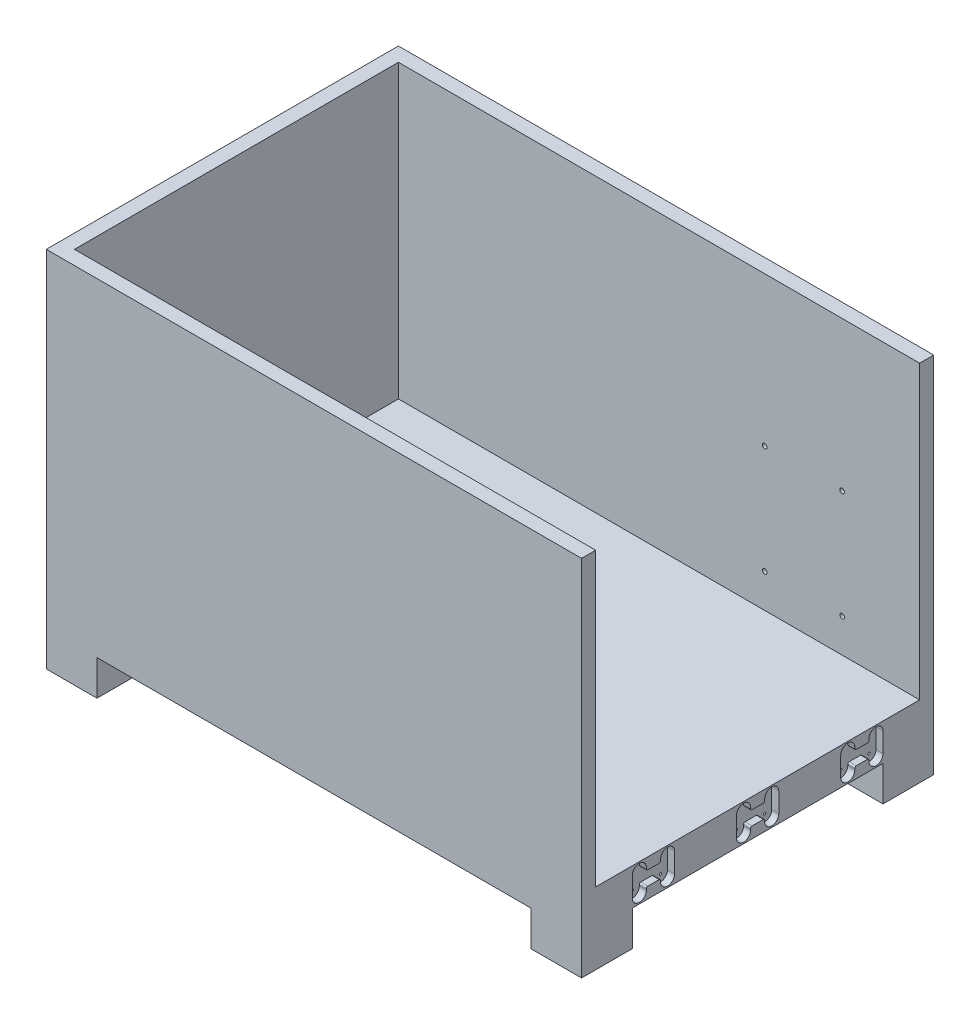
SolidWorks part; units mm, degrees
other "标注1"
sketch "草图15" plane through (-170.5512, -25, -92.4567) normal (0, 0, -1) x (-1, 0, 0)
other "细节项目1"
ref_plane "前视基准面" through (0, 0, 0) normal (0, 0, 1) x (1, 0, 0)
ref_plane "上视基准面" through (0, 0, 0) normal (0, 1, 0) x (1, 0, 0)
ref_plane "右视基准面" through (0, 0, 0) normal (1, 0, 0) x (0, 0, -1)
other "Configuration Table"
sketch "草图1" plane through (0, 0, 0) normal (0, 1, 0) x (1, 0, 0)
  line L1 (-170.5512, 92.4567) -> (209.4488, 92.4567)
  line L2 (-170.5512, 92.4567) -> (-170.5512, -157.5433)
  line L3 (-170.5512, -157.5433) -> (209.4488, -157.5433)
  line L4 (209.4488, 92.4567) -> (209.4488, -157.5433)
  dimension "D1" = 380
  dimension "D2" = 250
extrude "凸台-拉伸1" add sketch "草图1" along normal blind 233
sketch "草图2" plane through (0, 233, 0) normal (0, 1, 0) x (1, 0, 0)
  line L0 (19.4488, 92.4567) -> (19.4488, -157.5433) construction
  line L1 (209.4488, 92.4567) -> (-170.5512, 92.4567) construction
  line L2 (-170.5512, -157.5433) -> (209.4488, -157.5433) construction
  line L3 (-170.5512, 92.4567) -> (-170.5512, -157.5433) construction
  line L4 (-170.5512, -32.5433) -> (209.4488, -32.5433) construction
  line L5 (209.4488, -157.5433) -> (209.4488, 92.4567) construction
  line L18 (-160.5512, 82.4567) -> (-160.5512, -147.5433)
  line L19 (-160.5512, -147.5433) -> (199.4488, -147.5433)
  line L20 (199.4488, -147.5433) -> (199.4488, 82.4567)
  line L21 (199.4488, 82.4567) -> (-160.5512, 82.4567)
  line L22 (-160.5512, 82.4567) -> (-160.5512, -147.5433)
  line L23 (-160.5512, -147.5433) -> (199.4488, -147.5433)
  line L24 (199.4488, -147.5433) -> (199.4488, 82.4567)
  line L25 (199.4488, 82.4567) -> (-160.5512, 82.4567)
  dimension "D2" = 360
  dimension "D3" = 230
  dimension "D1" = 10
sketch "草图4" plane through (0, 0, 0) normal (0, -1, 0) x (1, 0, 0)
  line L0 (19.4488, 157.5433) -> (19.4488, -92.4567) construction
  line L1 (-170.5512, 157.5433) -> (-134.5512, 157.5433)
  line L2 (-170.5512, 157.5433) -> (-170.5512, 121.5433)
  line L3 (-170.5512, 121.5433) -> (-134.5512, 121.5433)
  line L4 (-134.5512, 157.5433) -> (-134.5512, 121.5433)
  line L5 (-170.5512, 157.5433) -> (209.4488, 157.5433) construction
  line L6 (209.4488, -92.4567) -> (-170.5512, -92.4567) construction
  line L7 (-170.5512, 32.5433) -> (209.4488, 32.5433) construction
  line L8 (-170.5512, -92.4567) -> (-170.5512, 157.5433) construction
  line L9 (209.4488, 157.5433) -> (209.4488, -92.4567) construction
  line L10 (209.4488, 121.5433) -> (173.4488, 121.5433)
  line L11 (173.4488, 157.5433) -> (173.4488, 121.5433)
  line L12 (209.4488, 157.5433) -> (173.4488, 157.5433)
  line L13 (209.4488, 157.5433) -> (209.4488, 121.5433)
  line L14 (209.4488, -92.4567) -> (209.4488, -56.4567)
  line L15 (209.4488, -92.4567) -> (173.4488, -92.4567)
  line L16 (173.4488, -92.4567) -> (173.4488, -56.4567)
  line L17 (209.4488, -56.4567) -> (173.4488, -56.4567)
  line L18 (-170.5512, -56.4567) -> (-134.5512, -56.4567)
  line L19 (-134.5512, -92.4567) -> (-134.5512, -56.4567)
  line L20 (-170.5512, -92.4567) -> (-134.5512, -92.4567)
  line L21 (-170.5512, -92.4567) -> (-170.5512, -56.4567)
  line L22 (-152.5512, 157.5433) -> (-152.5512, 121.5433) construction
  point P31 (-152.5512, 139.5433)
  point P33 (191.4488, 139.5433)
  point P35 (191.4488, -74.4567)
  point P36 (-152.5512, -74.4567)
  dimension "D1" = 36
  dimension "D2" = 344
  dimension "D3" = 214
extrude "凸台-拉伸2" add sketch "草图4" along normal blind 25
sketch "草图5" plane through (0, -25, 0) normal (0, -1, 0) x (1, 0, 0)
  line L0 (-152.5512, 157.5433) -> (-152.5512, 121.5433) construction
  line L3 (-134.5512, 157.5433) -> (-170.5512, 157.5433) construction
  line L4 (-170.5512, 121.5433) -> (-134.5512, 121.5433) construction
  line L6 (19.4488, 157.5433) -> (19.4488, -92.4567) construction
  line L7 (-134.5512, 157.5433) -> (173.4488, 157.5433) construction
  line L8 (173.4488, -92.4567) -> (-134.5512, -92.4567) construction
  line L9 (-170.5512, 32.5433) -> (209.4488, 32.5433) construction
  line L10 (-170.5512, -56.4567) -> (-170.5512, 121.5433) construction
  line L11 (209.4488, 121.5433) -> (209.4488, -56.4567) construction
  point P6 (-152.5512, 139.5433)
  point P20 (191.4488, 139.5433)
  point P22 (191.4488, -74.4567)
  point P23 (-152.5512, -74.4567)
hole_wizard "M6 螺纹孔1" positions "草图5" profile "草图6" tap size "M6" standard "GB"
sketch "草图6" plane through (-152.5512, -25, -74.4567) normal (1, 0, 0) x (0, 0, -1)
  line L0 (0, 0) -> (0, 16.5022)
  line L1 (0, 16.5022) -> (2.5, 15)
  line L2 (2.5, 15) -> (2.5, 0)
  line L5 (2.5, 0) -> (0, 0)
  line L10 (0, 16.5022) -> (-2.5, 15) construction
  line L11 (0, -6.35) -> (0, 107.95) construction
  dimension "螺纹孔钻头直径" = 5
  dimension "螺纹孔钻头深度" = 15
  dimension "导头角度" = 118
cosmetic thread "孔螺蚊线1" parameters "D1"=39, "D2"=6
cosmetic thread "孔螺蚊线2" parameters "D1"=39, "D2"=6
cosmetic thread "孔螺蚊线3" parameters "D1"=39, "D2"=6
cosmetic thread "孔螺蚊线4" parameters "D1"=39, "D2"=6
extrude "切除-拉伸1" cut sketch "草图2" against normal blind 207
sketch "草图7" plane through (0, 233, 0) normal (0, 1, 0) x (1, 0, 0)
  line L5 (199.4488, 82.4567) -> (199.4488, -147.5433)
  line L6 (199.4488, 82.4567) -> (209.4488, 82.4567)
  line L9 (209.4488, 82.4567) -> (209.4488, -147.5433)
  line L11 (209.4488, -157.5433) -> (209.4488, 92.4567) construction
  line L12 (199.4488, -147.5433) -> (209.4488, -147.5433)
sketch "草图11" plane through (0, 0, -92.4567) normal (0, 0, -1) x (-1, 0, 0)
  line L0 (-209.4488, 233) -> (-209.4488, -25) construction
  line L1 (-173.4488, 0) -> (134.5512, 0) construction
  point P0 (-154.4488, 127)
  point P1 (-99.4488, 127)
  point P2 (-154.4488, 50)
  point P3 (-99.4488, 50)
  dimension "D1" = 55
  dimension "D2" = 77
  dimension "D3" = 55
  dimension "D4" = 50
hole_wizard "M4 螺纹孔1" positions "草图11" profile "草图12" tap size "M4" standard "GB"
sketch "草图12" plane through (154.4488, 127, -92.4567) normal (1, 0, 0) x (0, 1, 0)
  line L0 (0, 0) -> (0, 10)
  line L1 (0, 10) -> (1.65, 10)
  line L2 (1.65, 10) -> (1.65, 0)
  line L5 (1.65, 0) -> (0, 0)
  line L11 (0, -6.35) -> (0, 107.95) construction
  dimension "通孔螺纹孔钻头直径" = 3.3
  dimension "通孔螺纹孔钻头深度" = 10
cosmetic thread "孔螺蚊线5" parameters "D2"=4
cosmetic thread "孔螺蚊线6" parameters "D2"=4
cosmetic thread "孔螺蚊线7" parameters "D2"=4
cosmetic thread "孔螺蚊线8" parameters "D2"=4
extrude "切除-拉伸3" cut sketch "草图7" along direction (0, 1, 0) on the side against the normal up to surface (207 mm away)
sketch "草图22" plane through (209.4488, 0, 0) normal (1, 0, 0) x (0, 0, -1)
  line L0 (-101.5433, 5.9795) -> (-101.5433, 6.9795)
  line L3 (-91.5433, 5.9795) -> (-91.5433, 19.9795)
  line L6 (-102.5433, 7.9795) -> (-110.5433, 7.9795)
  line L9 (-110.5433, 17.9795) -> (-102.5433, 17.9795)
  line L12 (-121.5433, 5.9795) -> (-121.5433, 19.9795)
  line L13 (-111.5433, 5.9795) -> (-111.5433, 6.9795)
  line L14 (-101.5433, 19.9795) -> (-101.5433, 18.9795)
  line L15 (-111.5433, 19.9795) -> (-111.5433, 18.9795)
  line L16 (-27.5433, 5.9795) -> (-27.5433, 6.9795)
  line L17 (82.4567, 26) -> (-147.5433, 26) construction
  line L18 (-121.5433, 0) -> (-121.5433, 26)
  line L19 (-121.5433, 0) -> (56.4567, 0)
  line L20 (56.4567, 0) -> (56.4567, 26)
  line L21 (56.4567, 26) -> (-121.5433, 26)
  line L22 (-28.5433, 7.9795) -> (-36.5433, 7.9795)
  line L23 (-37.5433, 5.9795) -> (-37.5433, 6.9795)
  line L24 (-47.5433, 5.9795) -> (-47.5433, 19.9795)
  line L25 (-37.5433, 19.9795) -> (-37.5433, 18.9795)
  line L26 (-36.5433, 17.9795) -> (-28.5433, 17.9795)
  line L27 (-27.5433, 19.9795) -> (-27.5433, 18.9795)
  line L28 (-17.5433, 5.9795) -> (-17.5433, 19.9795)
  line L29 (46.4567, 5.9795) -> (46.4567, 6.9795)
  line L30 (45.4567, 7.9795) -> (37.4567, 7.9795)
  line L31 (36.4567, 5.9795) -> (36.4567, 6.9795)
  line L32 (26.4567, 5.9795) -> (26.4567, 19.9795)
  line L33 (36.4567, 19.9795) -> (36.4567, 18.9795)
  line L34 (37.4567, 17.9795) -> (45.4567, 17.9795)
  line L35 (46.4567, 19.9795) -> (46.4567, 18.9795)
  line L36 (56.4567, 5.9795) -> (56.4567, 19.9795)
  arc A8 (-101.5433, 5.9795) -> (-91.5433, 5.9795) centre (-96.5433, 5.9795) ccw
  arc A9 (-91.5433, 19.9795) -> (-101.5433, 19.9795) centre (-96.5433, 19.9795) ccw
  circle A10 centre (-96.5433, 5.9795) radius 1
  circle A11 centre (-96.5433, 19.9795) radius 1
  arc A12 (-121.5433, 5.9795) -> (-111.5433, 5.9795) centre (-116.5433, 5.9795) ccw
  arc A13 (-111.5433, 19.9795) -> (-121.5433, 19.9795) centre (-116.5433, 19.9795) ccw
  arc A14 (-102.5433, 7.9795) -> (-101.5433, 6.9795) centre (-102.5433, 6.9795) cw
  arc A15 (-102.5433, 17.9795) -> (-101.5433, 18.9795) centre (-102.5433, 18.9795) ccw
  arc A16 (-110.5433, 7.9795) -> (-111.5433, 6.9795) centre (-110.5433, 6.9795) ccw
  arc A17 (-110.5433, 17.9795) -> (-111.5433, 18.9795) centre (-110.5433, 18.9795) cw
  circle A18 centre (-116.5433, 5.9795) radius 1
  circle A19 centre (-116.5433, 19.9795) radius 1
  arc A20 (-28.5433, 7.9795) -> (-27.5433, 6.9795) centre (-28.5433, 6.9795) cw
  arc A21 (-36.5433, 7.9795) -> (-37.5433, 6.9795) centre (-36.5433, 6.9795) ccw
  arc A22 (-47.5433, 5.9795) -> (-37.5433, 5.9795) centre (-42.5433, 5.9795) ccw
  arc A23 (-37.5433, 19.9795) -> (-47.5433, 19.9795) centre (-42.5433, 19.9795) ccw
  arc A24 (-36.5433, 17.9795) -> (-37.5433, 18.9795) centre (-36.5433, 18.9795) cw
  arc A25 (-28.5433, 17.9795) -> (-27.5433, 18.9795) centre (-28.5433, 18.9795) ccw
  arc A26 (-17.5433, 19.9795) -> (-27.5433, 19.9795) centre (-22.5433, 19.9795) ccw
  arc A27 (-27.5433, 5.9795) -> (-17.5433, 5.9795) centre (-22.5433, 5.9795) ccw
  circle A28 centre (-42.5433, 19.9795) radius 1
  circle A29 centre (-42.5433, 5.9795) radius 1
  circle A30 centre (-22.5433, 19.9795) radius 1
  circle A31 centre (-22.5433, 5.9795) radius 1
  arc A32 (45.4567, 7.9795) -> (46.4567, 6.9795) centre (45.4567, 6.9795) cw
  arc A33 (37.4567, 7.9795) -> (36.4567, 6.9795) centre (37.4567, 6.9795) ccw
  arc A34 (26.4567, 5.9795) -> (36.4567, 5.9795) centre (31.4567, 5.9795) ccw
  arc A35 (36.4567, 19.9795) -> (26.4567, 19.9795) centre (31.4567, 19.9795) ccw
  arc A36 (37.4567, 17.9795) -> (36.4567, 18.9795) centre (37.4567, 18.9795) cw
  arc A37 (45.4567, 17.9795) -> (46.4567, 18.9795) centre (45.4567, 18.9795) ccw
  arc A38 (56.4567, 19.9795) -> (46.4567, 19.9795) centre (51.4567, 19.9795) ccw
  arc A39 (46.4567, 5.9795) -> (56.4567, 5.9795) centre (51.4567, 5.9795) ccw
  circle A40 centre (31.4567, 19.9795) radius 1
  circle A41 centre (31.4567, 5.9795) radius 1
  circle A42 centre (51.4567, 19.9795) radius 1
  circle A43 centre (51.4567, 5.9795) radius 1
  point P2 (-121.5433, 13)
  dimension "D1" = 178
  dimension "D2" = 26
  dimension "D3" = 3
hole_wizard "M2 螺纹孔1" positions "3D草图2" profile "草图25" tap size "M2" standard "GB"
sketch3d "3D草图2"
  point P0 (209.4488, 19.9795, 116.5433)
  point P3 (209.4488, 5.9795, 116.5433)
  point P6 (209.4488, 5.9795, 96.5433)
  point P9 (209.4488, 19.9795, 96.5433)
  point P12 (209.4488, 19.9795, 42.5433)
  point P15 (209.4488, 5.9795, 42.5433)
  point P18 (209.4488, 19.9795, 22.5433)
  point P21 (209.4488, 5.9795, 22.5433)
  point P24 (209.4488, 19.9795, -31.4567)
  point P27 (209.4488, 19.9795, -51.4567)
  point P30 (209.4488, 5.9795, -31.4567)
  point P33 (209.4488, 5.9795, -51.4567)
sketch "草图25" plane through (209.4488, 19.9795, 116.5433) normal (0, 1, 0) x (0, 0, -1)
  line L0 (0, 0) -> (0, 15.4807)
  line L1 (0, 15.4807) -> (0.8, 15)
  line L2 (0.8, 15) -> (0.8, 0)
  line L5 (0.8, 0) -> (0, 0)
  line L10 (0, 15.4807) -> (-0.8, 15) construction
  line L11 (0, -6.35) -> (0, 107.95) construction
  dimension "螺纹孔钻头直径" = 1.6
  dimension "螺纹孔钻头深度" = 15
  dimension "导头角度" = 118
cosmetic thread "孔螺蚊线9" parameters "D1"=15, "D2"=2
cosmetic thread "孔螺蚊线10" parameters "D1"=15, "D2"=2
cosmetic thread "孔螺蚊线11" parameters "D1"=15, "D2"=2
cosmetic thread "孔螺蚊线12" parameters "D1"=15, "D2"=2
cosmetic thread "孔螺蚊线13" parameters "D1"=15, "D2"=2
cosmetic thread "孔螺蚊线14" parameters "D1"=15, "D2"=2
cosmetic thread "孔螺蚊线15" parameters "D1"=15, "D2"=2
cosmetic thread "孔螺蚊线16" parameters "D1"=15, "D2"=2
cosmetic thread "孔螺蚊线17" parameters "D1"=15, "D2"=2
cosmetic thread "孔螺蚊线18" parameters "D1"=15, "D2"=2
cosmetic thread "孔螺蚊线19" parameters "D1"=15, "D2"=2
cosmetic thread "孔螺蚊线20" parameters "D1"=15, "D2"=2
extrude "切除-拉伸6" cut sketch "草图22" against normal blind 5 contours A11 | A18 | A10 | L9 A17 L15 A13 L12 A12 L13 A16 L6 A14 L0 A8 L3 A9 L14 A15 A19 A18 A10 A11 | A28 | A30 | A31 | A29 | L16 A27 L28 A26 L27 A25 L26 A24 L25 A23 L24 A22 L23 A21 L22 A20 A31 A30 A29 A28 | A40 | A42 | A41 | A43 | L29 A39 L20 A38 L35 A37 L34 A36 L33 A35 L32 A34 L31 A33 L30 A32 A43 A42 A41 A40
